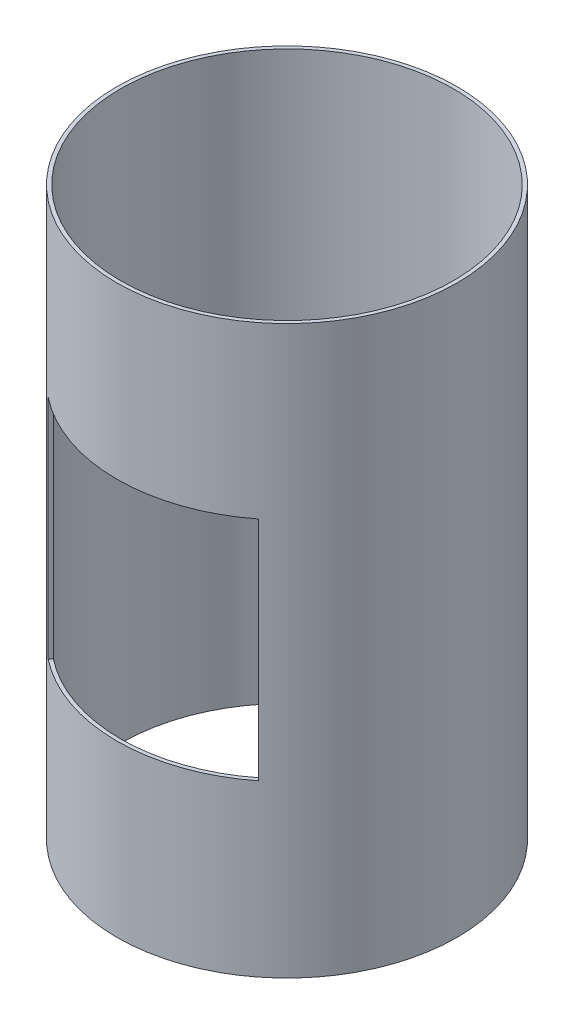
SolidWorks part; units mm, degrees
ref_plane "Front Plane" through (0, 0, 0) normal (0, 0, 1) x (1, 0, 0)
ref_plane "Top Plane" through (0, 0, 0) normal (0, 1, 0) x (1, 0, 0)
ref_plane "Right Plane" through (0, 0, 0) normal (1, 0, 0) x (0, 0, -1)
sketch "Sketch1" plane through (0, 0, 0) normal (0, 1, 0) x (1, 0, 0)
  circle A0 centre (0, 0) radius 76.2
  circle A1 centre (0, 0) radius 74.549
  dimension "D1" = 152.4
  dimension "D2" = 149.098
extrude "Boss-Extrude1" add sketch "Sketch1" along normal blind 254
sketch3d "3DSketch2" plane through (0, 0, 0) normal (0, 0, 1) x (1, 0, 0)
sketch "Sketch2" plane through (0, 0, 0) normal (0, 0, 1) x (1, 0, 0)
  line L0 (-76.2, 254) -> (-76.2, 0) construction
  line L1 (-50.8, 177.8) -> (50.8, 177.8)
  line L2 (-50.8, 177.8) -> (-50.8, 76.2)
  line L3 (-50.8, 76.2) -> (50.8, 76.2)
  line L4 (50.8, 177.8) -> (50.8, 76.2)
  line L5 (76.2, 0) -> (76.2, 254) construction
  line L6 (-76.2, 0) -> (76.2, 0) construction
  dimension "D1" = 25.4
  dimension "D2" = 25.4
  dimension "D3" = 101.6
  dimension "D4" = 76.2
wrap "Wrap2" sketch "Sketch2" wrap type deboss source sketch "Sketch2" thickness 3.302 face at (0, 254, 76.2) parameters "D1"=3.302
